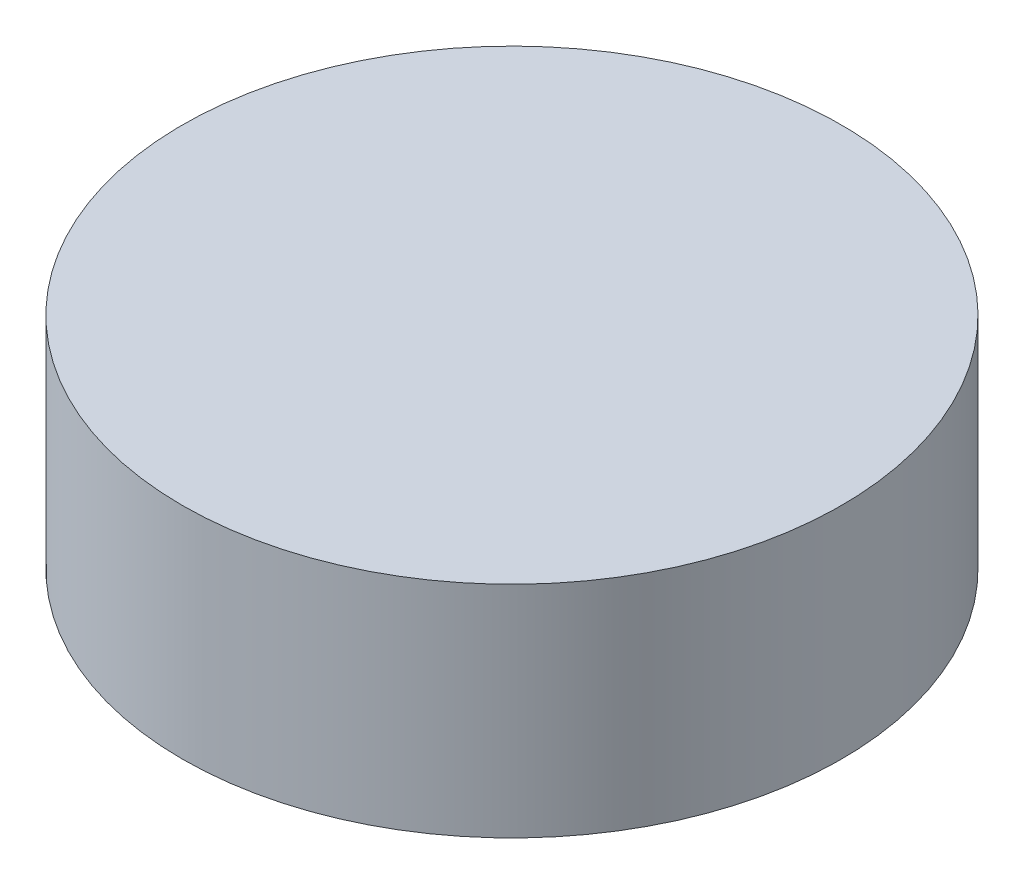
SolidWorks part; units mm, degrees
ref_plane "Front" through (0, 0, 0) normal (0, 0, 1) x (1, 0, 0)
ref_plane "Top" through (0, 0, 0) normal (0, 1, 0) x (1, 0, 0)
ref_plane "Right" through (0, 0, 0) normal (1, 0, 0) x (0, 0, -1)
other "Configuration Table"
sketch "Esquisse1" plane through (0, 0, 0) normal (0, 1, 0) x (1, 0, 0)
  circle A0 centre (0, 0) radius 3
  dimension "D1" = 6
extrude "Boss.-Extru.1" add sketch "Esquisse1" along normal blind 2
